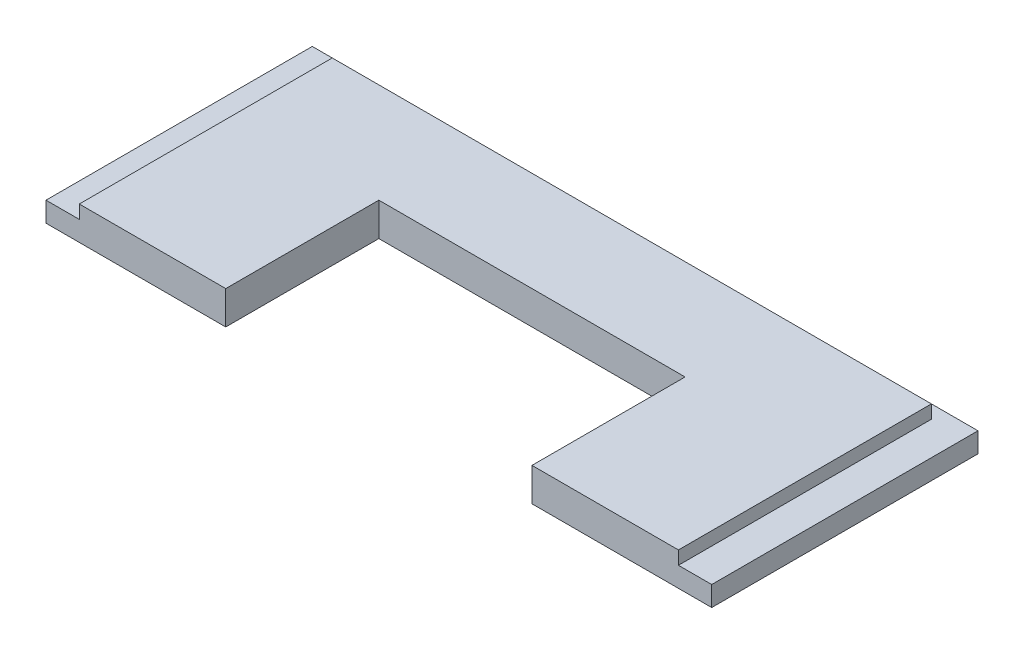
SolidWorks part; units mm, degrees
material "Copper"
ref_plane "Front Plane" through (0, 0, 0) normal (0, 0, 1) x (1, 0, 0)
ref_plane "Top Plane" through (0, 0, 0) normal (0, 1, 0) x (1, 0, 0)
ref_plane "Right Plane" through (0, 0, 0) normal (1, 0, 0) x (0, 0, -1)
sketch "Sketch1" plane through (0, 0, 0) normal (0, 1, 0) x (1, 0, 0)
  line L1 (0, 0) -> (-100, 0)
  line L2 (0, 0) -> (0, 40)
  line L3 (0, 40) -> (-100, 40)
  line L4 (-100, 0) -> (-100, 40)
  line L5 (-73, 0) -> (-27, 0)
  line L6 (-73, 0) -> (-73, 23)
  line L7 (-73, 23) -> (-27, 23)
  line L8 (-27, 0) -> (-27, 23)
  point P9 (-50, 23)
  point P10 (-50, 40)
  dimension "D1" = 100
  dimension "D2" = 40
  dimension "D3" = 46
  dimension "D4" = 0
  dimension "D5" = 23
extrude "Boss-Extrude1" add sketch "Sketch1" along normal blind 5 contours L8 L1 L2 L3 L4 L6 L7
sketch "Sketch2" plane through (0, 5, 0) normal (0, 1, 0) x (1, 0, 0)
  line L0 (0, 40) -> (-100, 40) construction
  line L1 (-100, 0) -> (-95, 0)
  line L2 (-100, 0) -> (-100, 40)
  line L3 (-100, 40) -> (-95, 40)
  line L4 (-95, 0) -> (-95, 40)
  line L6 (0, 0) -> (-5, 0)
  line L7 (0, 0) -> (0, 40)
  line L8 (0, 40) -> (-5, 40)
  line L9 (-5, 0) -> (-5, 40)
  line L10 (-95, 40) -> (-5, 40)
  line L11 (-95, 40) -> (-95, 38)
  line L12 (-95, 38) -> (-5, 38)
  line L13 (-5, 40) -> (-5, 38)
  line M4 (-27, 0) -> (0, 0)
  line M5 (0, 0) -> (0, 40)
  line M6 (0, 40) -> (-100, 40)
  line M7 (-100, 40) -> (-100, 0)
  line M8 (-100, 0) -> (-73, 0)
  dimension "D1" = 5
  dimension "D2" = 2
extrude "Cut-Extrude1" cut sketch "Sketch2" against normal blind 2 contours L4 M8 M6 M7 | L4 L12 L9 M6 | L9 M4 M5 M6
